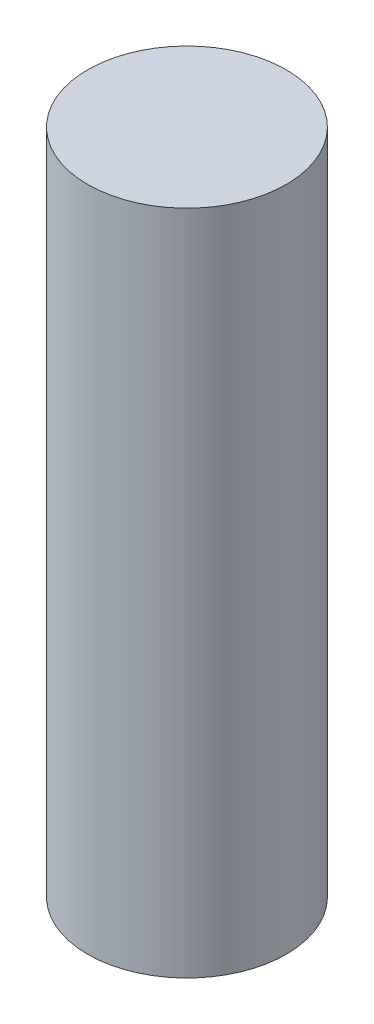
SolidWorks part; units mm, degrees
ref_plane "Front Plane" through (0, 0, 0) normal (0, 0, 1) x (1, 0, 0)
ref_plane "Top Plane" through (0, 0, 0) normal (0, 1, 0) x (1, 0, 0)
ref_plane "Right Plane" through (0, 0, 0) normal (1, 0, 0) x (0, 0, -1)
sketch "Sketch1" plane through (0, 0, 0) normal (0, 1, 0) x (1, 0, 0)
  circle A0 centre (0, 0) radius 1.49
  dimension "D1" = 2.98
extrude "Boss-Extrude1" add sketch "Sketch1" along normal blind 10
